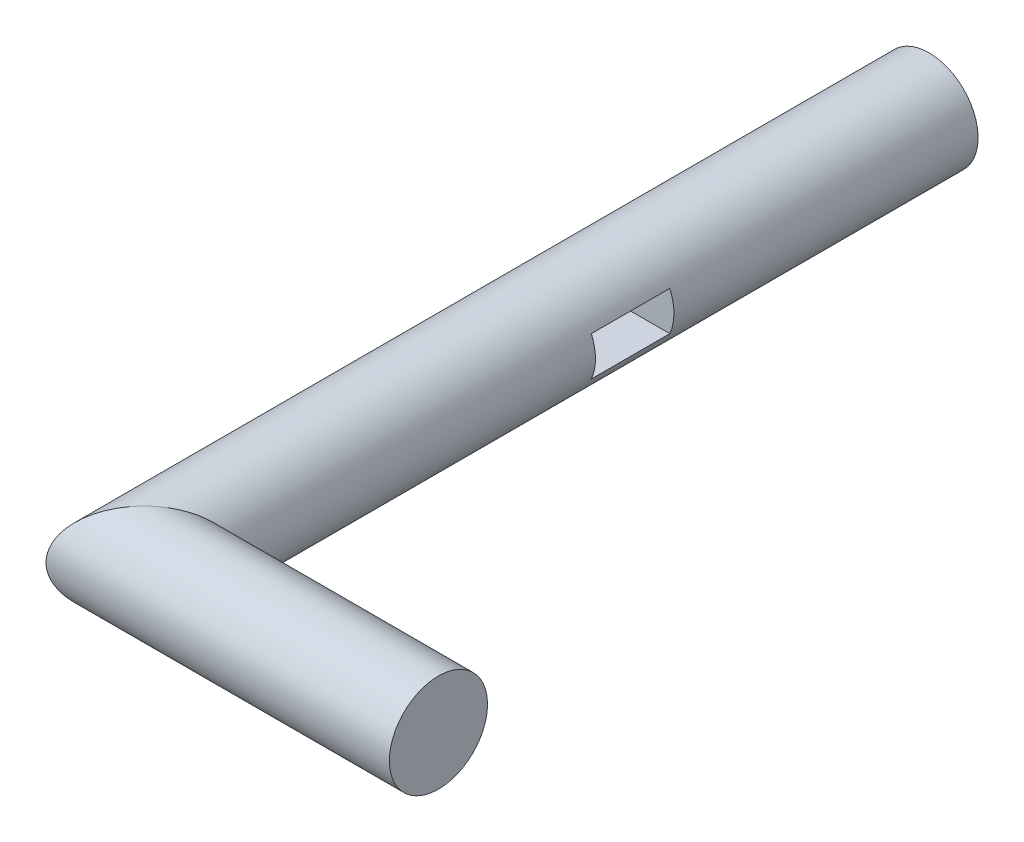
SolidWorks part; units mm, degrees
ref_plane "Front Plane" through (0, 0, 0) normal (0, 0, 1) x (1, 0, 0)
ref_plane "Top Plane" through (0, 0, 0) normal (0, 1, 0) x (1, 0, 0)
ref_plane "Right Plane" through (0, 0, 0) normal (1, 0, 0) x (0, 0, -1)
sketch "Sketch2" plane through (0, 0, 0) normal (0, 1, 0) x (1, 0, 0)
  line L0 (0, -10) -> (0, 70)
  line L2 (0, -10) -> (30, -10)
  point P7 (0, -10)
  dimension "D1" = 10
  dimension "D2" = 70
  dimension "D3" = 30
sweep "Sweep2" add path "Sketch2" circular profile diameter 10 parameters "D3"=10
sketch "Sketch4" plane through (0, 0, 0) normal (1, 0, 0) x (0, 0, -1)
  line L0 (35, -2) -> (35, 2) construction
  line L1 (31, 2) -> (39, 2)
  line L2 (31, 2) -> (31, -2)
  line L3 (31, -2) -> (39, -2)
  line L4 (39, 2) -> (39, -2)
  line L5 (0, 0) -> (0, 3.5037) construction
  line L6 (70, 0) -> (70, 4.3086) construction
  line L7 (70, -5) -> (70, 5) construction
  line L8 (0, 0) -> (35, 0) construction
  line L9 (35, 0) -> (70, 0) construction
  point P4 (31, 0)
  dimension "D1" = 4
  dimension "D2" = 8
extrude "Cut-Extrude1" cut sketch "Sketch4" against normal through all both and the other way through all
